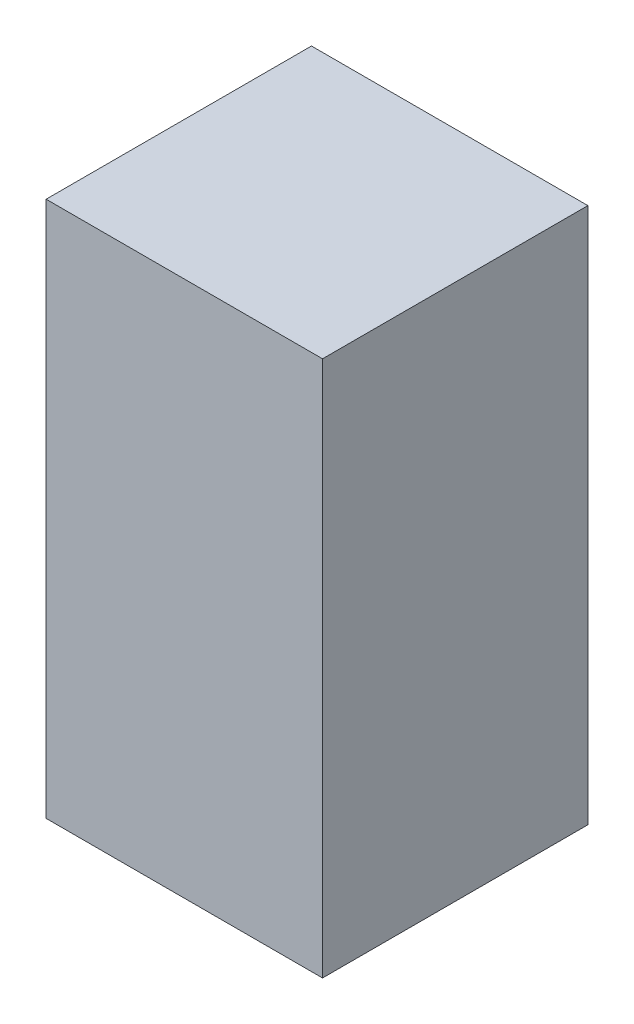
SolidWorks part; units mm, degrees
ref_plane "Front Plane" through (0, 0, 0) normal (0, 0, 1) x (1, 0, 0)
ref_plane "Top Plane" through (0, 0, 0) normal (0, 1, 0) x (1, 0, 0)
ref_plane "Right Plane" through (0, 0, 0) normal (1, 0, 0) x (0, 0, -1)
sketch "Sketch1" plane through (0, 0, 0) normal (0, 0, 1) x (1, 0, 0)
  line L1 (0, 0) -> (1270, 0)
  line L2 (0, 0) -> (0, 2463.8)
  line L3 (0, 2463.8) -> (1270, 2463.8)
  line L4 (1270, 0) -> (1270, 2463.8)
  dimension "D1" = 1270
  dimension "D2" = 2463.8
extrude "Boss-Extrude1" add sketch "Sketch1" along normal blind 1219.2
